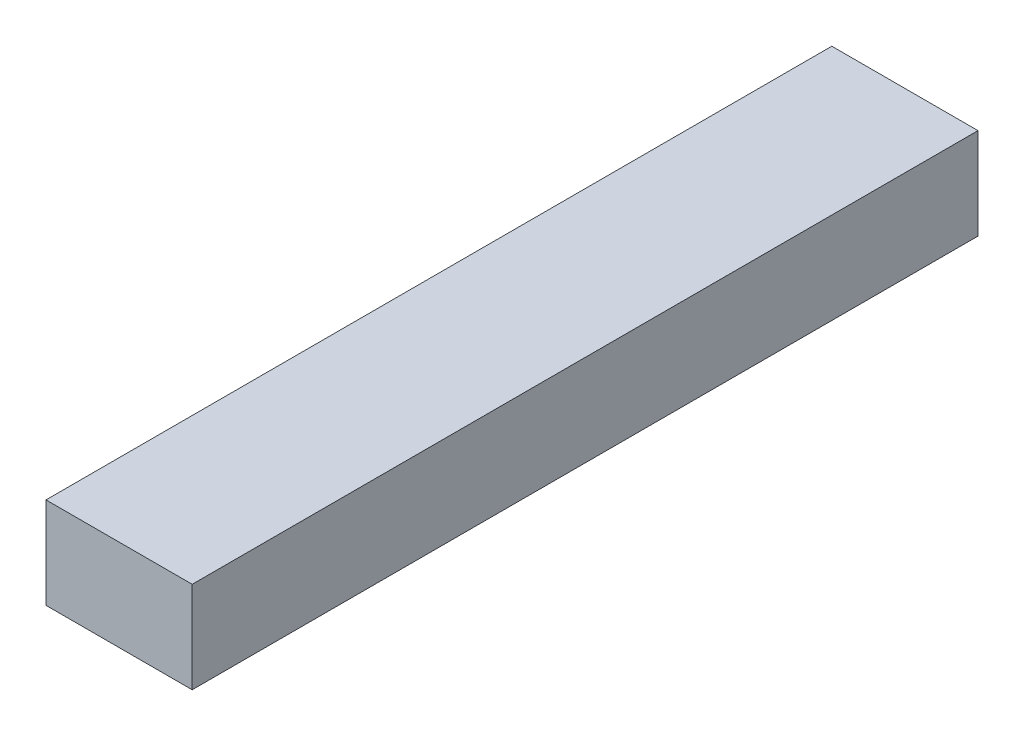
SolidWorks part; units mm, degrees
ref_plane "Front Plane" through (0, 0, 0) normal (0, 0, 1) x (1, 0, 0)
ref_plane "Top Plane" through (0, 0, 0) normal (0, 1, 0) x (1, 0, 0)
ref_plane "Right Plane" through (0, 0, 0) normal (1, 0, 0) x (0, 0, -1)
sketch "Sketch1" plane through (0, 0, 0) normal (0, 0, 1) x (1, 0, 0)
  line L1 (-8, -5) -> (8, -5)
  line L2 (-8, -5) -> (-8, 5)
  line L3 (-8, 5) -> (8, 5)
  line L4 (8, -5) -> (8, 5)
  line L5 (-8, -5) -> (8, 5) construction
  line L6 (-8, 5) -> (8, -5) construction
  point P0 (0, 0)
extrude "Boss-Extrude1" add sketch "Sketch1" along normal blind 86
